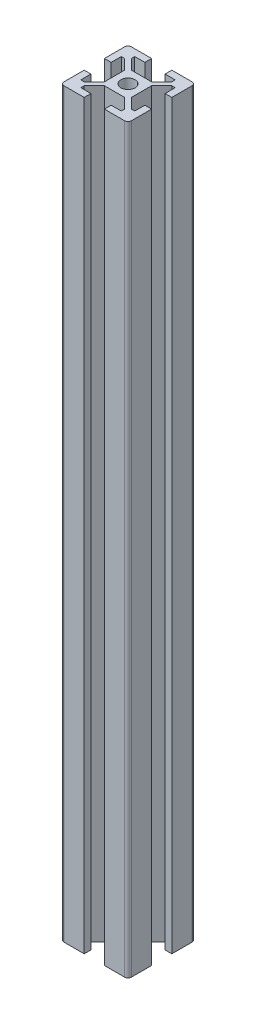
SolidWorks part; units mm, degrees
ref_plane "Front Plane" through (0, 0, 0) normal (0, 0, 1) x (1, 0, 0)
ref_plane "Top Plane" through (0, 0, 0) normal (0, 1, 0) x (1, 0, 0)
ref_plane "Right Plane" through (0, 0, 0) normal (1, 0, 0) x (0, 0, -1)
sketch "Sketch1" plane through (0, 0, 0) normal (0, 1, 0) x (1, 0, 0)
  line L5 (-3, 10) -> (-10, 10)
  line L6 (-4, 3) -> (-7, 6)
  line L7 (-4, -4) -> (4, -4)
  line L8 (-4, -4) -> (-4, 4)
  line L9 (-4, 4) -> (4, 4)
  line L10 (4, -4) -> (4, 4)
  line L11 (-8, 6) -> (-7, 6)
  line L12 (-8, 6) -> (-8, 3)
  line L16 (-3, 8) -> (-3, 10)
  line L21 (-8, 3) -> (-10, 3)
  line L22 (-6, 8) -> (-6, 7)
  line L23 (-10, 3) -> (-10, 10)
  line L24 (-3, 4) -> (-6, 7)
  line L25 (3, 10) -> (10, 10)
  line L26 (6, 8) -> (3, 8)
  line L27 (-6, 8) -> (-3, 8)
  line L28 (3, 8) -> (3, 10)
  line L29 (-10, 10) -> (-4, 4)
  line L30 (6, 8) -> (6, 7)
  line L31 (3, 4) -> (6, 7)
  line L32 (4, 3) -> (7, 6)
  line L33 (8, 6) -> (7, 6)
  line L34 (8, 6) -> (8, 3)
  line L35 (8, 3) -> (10, 3)
  line L36 (10, 3) -> (10, 10)
  line L37 (10, -3) -> (10, -10)
  line L38 (8, -6) -> (8, -3)
  line L39 (8, -3) -> (10, -3)
  line L40 (8, -6) -> (7, -6)
  line L41 (4, -3) -> (7, -6)
  line L42 (3, -4) -> (6, -7)
  line L43 (6, -8) -> (6, -7)
  line L44 (6, -8) -> (3, -8)
  line L45 (3, -8) -> (3, -10)
  line L46 (3, -10) -> (10, -10)
  line L47 (-3, -10) -> (-10, -10)
  line L48 (-6, -8) -> (-3, -8)
  line L49 (-3, -8) -> (-3, -10)
  line L50 (-6, -8) -> (-6, -7)
  line L51 (-3, -4) -> (-6, -7)
  line L52 (-4, -3) -> (-7, -6)
  line L53 (-8, -6) -> (-7, -6)
  line L54 (-8, -6) -> (-8, -3)
  line L55 (-8, -3) -> (-10, -3)
  line L56 (-10, -3) -> (-10, -10)
  circle A0 centre (0, 0) radius 2.1
  point P0 (0, 0)
  point P55 (0, 0)
  dimension "D3" = 3
  dimension "D1" = 4.2
  dimension "D2" = 4
  dimension "D4" = 4
  dimension "D5" = 6
  dimension "D7" = 8
  dimension "D8" = 10
  dimension "D6" = 4
extrude "Boss-Extrude1" add sketch "Sketch1" along normal blind 220 contours L29 L23 L21 L12 L11 L6 L8 | L5 L29 L9 L24 L22 L27 L16 | L35 L36 L25 L28 L26 L30 L31 L9 L10 L32 L33 L34 | L7 L10 L9 L8 A0 | L45 L46 L37 L39 L38 L40 L41 L10 L7 L42 L43 L44 | L55 L56 L47 L49 L48 L50 L51 L7 L8 L52 L53 L54
fillet "Fillet1" radius 1 4 edges at (-10, 110, 10) (-10, 110, -10) (10, 110, -10) (10, 110, 10)
ref_plane "Plane1" through (0, 110, 0) normal (0, -1, 0) x (-1, 0, 0)
